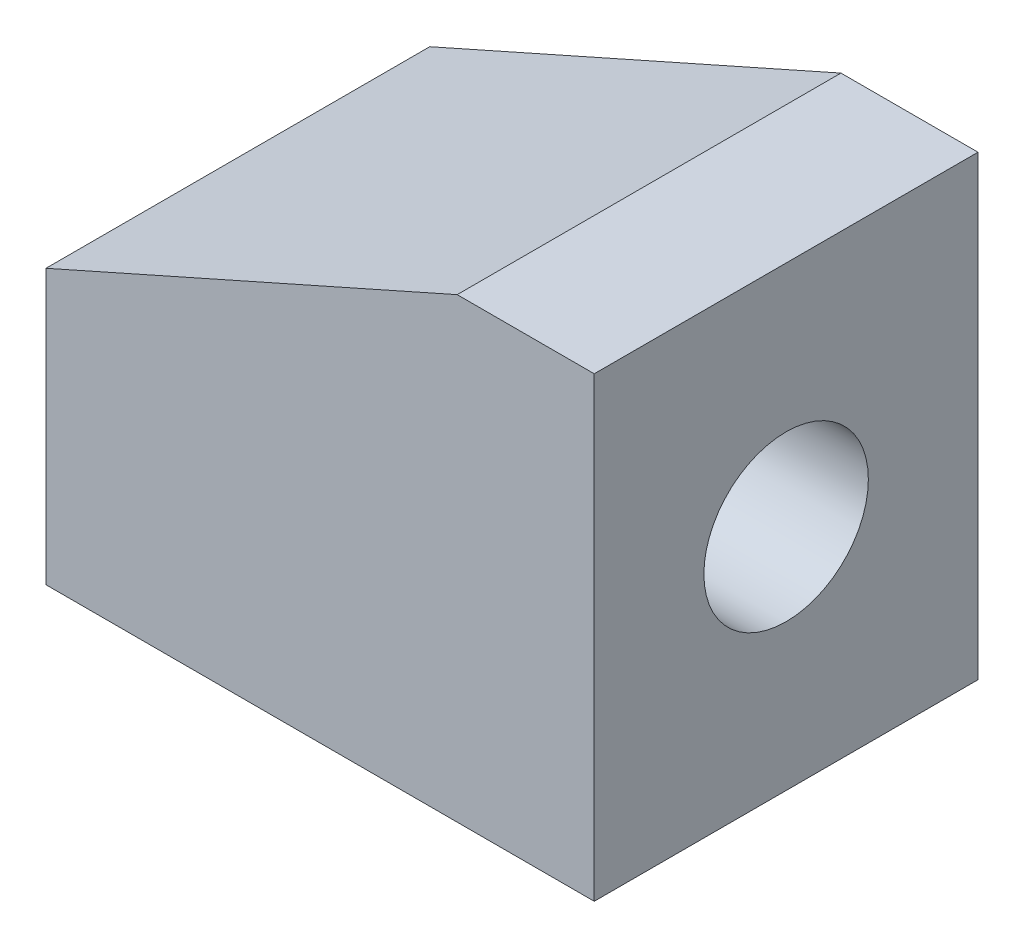
SolidWorks part; units mm, degrees
ref_plane "Front Plane" through (0, 0, 0) normal (0, 0, 1) x (1, 0, 0)
ref_plane "Top Plane" through (0, 0, 0) normal (0, 1, 0) x (1, 0, 0)
ref_plane "Right Plane" through (0, 0, 0) normal (1, 0, 0) x (0, 0, -1)
sketch "Sketch1" plane through (0, 0, 0) normal (0, 0, 1) x (1, 0, 0)
  line L0 (0, 0) -> (-60, 0)
  line L1 (-60, 0) -> (-60, 30)
  line L2 (-60, 30) -> (-15, 50)
  line L3 (-15, 50) -> (0, 50)
  line L4 (0, 50) -> (0, 0)
  dimension "D1" = 60
  dimension "D2" = 50
  dimension "D3" = 15
  dimension "D4" = 30
extrude "Boss-Extrude1" add sketch "Sketch1" along normal mid plane 42
sketch "Sketch2" plane through (0, 0, 0) normal (1, 0, 0) x (0, 0, -1)
  circle A0 centre (0, 25) radius 9
  dimension "D1" = 18
  dimension "D2" = 25
extrude "Cut-Extrude1" cut sketch "Sketch2" against normal mid plane 40
